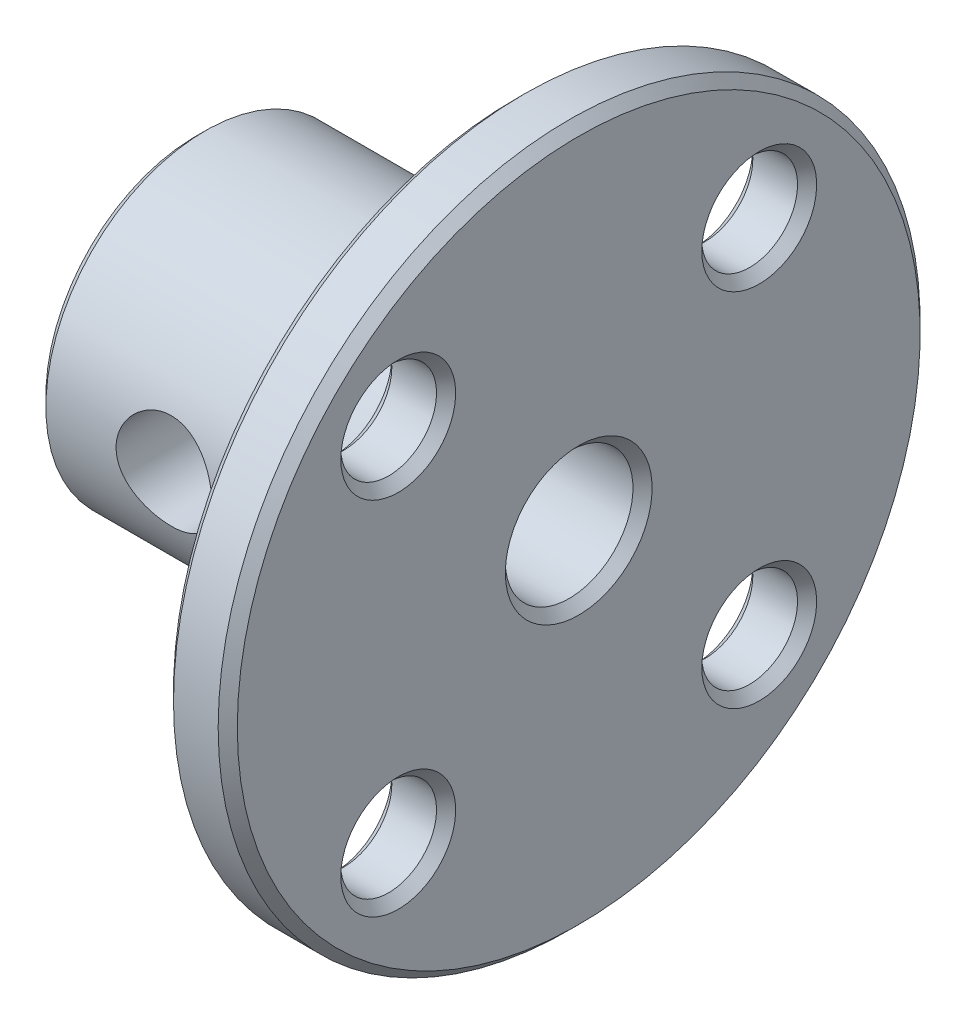
SolidWorks part; units mm, degrees
material "AISI 304"
ref_plane "Front Plane" through (0, 0, 0) normal (0, 0, 1) x (1, 0, 0)
ref_plane "Top Plane" through (0, 0, 0) normal (0, 1, 0) x (1, 0, 0)
ref_plane "Right Plane" through (0, 0, 0) normal (1, 0, 0) x (0, 0, -1)
sketch "Sketch1" plane through (0, 0, 0) normal (0, 0, 1) x (1, 0, 0)
  line L0 (-6, 0) -> (6, 0)
  line L1 (-6, 0) -> (-6, 5)
  line L2 (-6, 5) -> (4, 5)
  line L3 (4, 5) -> (4, 11)
  line L4 (4, 11) -> (6, 11)
  line L5 (6, 11) -> (6, 0)
  point P4 (0, 0)
  dimension "D1" = 12
  dimension "D2" = 5
  dimension "D3" = 10
  dimension "D4" = 11
revolve "Revolve1" add sketch "Sketch1" angle 360 about L0
sketch "Sketch2" plane through (-6, 0, 0) normal (-1, 0, 0) x (0, 0, 1)
  line L0 (-5.6569, 5.6569) -> (0, 0) construction
  line L1 (0, 0) -> (0, 8) construction
  circle A0 centre (0, 0) radius 2
  circle A1 centre (0, 0) radius 8 construction
  circle A6 centre (-5.6569, 5.6569) radius 1.5
  circle A7 centre (5.6569, 5.6569) radius 1.5
  circle A8 centre (5.6569, -5.6569) radius 1.5
  circle A9 centre (-5.6569, -5.6569) radius 1.5
  dimension "D1" = 4
  dimension "D2" = 16
  dimension "D3" = 45
  dimension "D4" = 3
  dimension "D5" = 4
extrude "Cut-Extrude1" cut sketch "Sketch2" against normal blind 12
chamfer "Chamfer1" distance 0.3 angle 45 14 edges at (4, 0, 11) (4, 0, 5) (4, 5.6569, -7.1569) (6, 0, 11) (6, 0, 2) (6, 5.6569, -4.1569) (-6, 0, 5) (-6, 0, 2) (4, 5.6569, 4.1569) (4, -5.6569, 4.1569) (4, -5.6569, -7.1569) (6, 5.6569, 7.1569) (6, -5.6569, 7.1569) (6, -5.6569, -4.1569)
sketch "Sketch3" plane through (0, 0, 0) normal (0, 0, 1) x (1, 0, 0)
  line L0 (-6, 0) -> (-2, 0) construction
  line L1 (-6, 4.7) -> (-6, -4.7) construction
  circle A0 centre (-2, 0) radius 1.5
  dimension "D2" = 3
  dimension "D1" = 4
extrude "Cut-Extrude2" cut sketch "Sketch3" against normal mid plane 12
